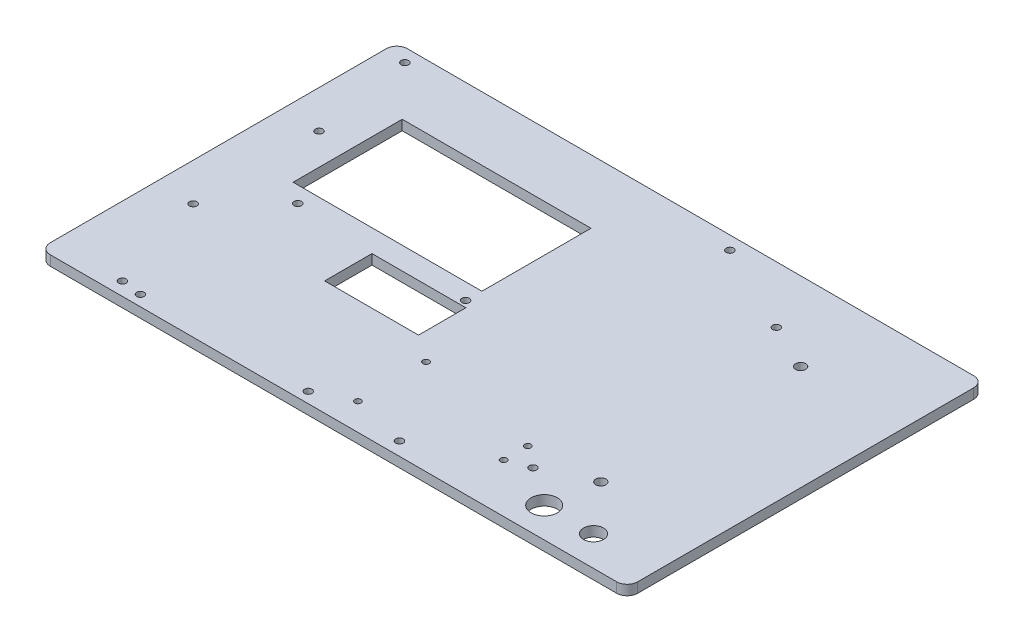
SolidWorks part; units mm, degrees
material "Acrylic (Medium-high impact)"
ref_plane "Front Plane" through (0, 0, 0) normal (0, 0, 1) x (1, 0, 0)
ref_plane "Top Plane" through (0, 0, 0) normal (0, 1, 0) x (1, 0, 0)
ref_plane "Right Plane" through (0, 0, 0) normal (1, 0, 0) x (0, 0, -1)
sketch "Sketch1" plane through (0, 0, 0) normal (0, 1, 0) x (1, 0, 0)
  line L1 (-135, 85.09) -> (135, 85.09)
  line L2 (-140, 80.09) -> (-140, -80.09)
  line L3 (-135, -85.09) -> (135, -85.09)
  line L4 (140, 80.09) -> (140, -80.09)
  line L5 (-140, 85.09) -> (140, -85.09) construction
  line L6 (-140, -85.09) -> (140, 85.09) construction
  arc A0 (-135, 85.09) -> (-140, 80.09) centre (-135, 80.09) ccw
  arc A1 (-140, -80.09) -> (-135, -85.09) centre (-135, -80.09) ccw
  arc A2 (135, -85.09) -> (140, -80.09) centre (135, -80.09) ccw
  arc A3 (135, 85.09) -> (140, 80.09) centre (135, 80.09) cw
  point P0 (0, 0)
  dimension "D3" = 5
  dimension "D1" = 170.18
  dimension "D2" = 280
extrude "Boss-Extrude1" add sketch "Sketch1" along normal blind 4.7625
sketch "Sketch2" plane through (0, 0, 0) normal (0, 1, 0) x (1, 0, 0)
  line L0 (-122, 30) -> (-122, -30) construction
  line L1 (68, 58) -> (68, -58) construction
  line L2 (-140, 80.09) -> (-140, -80.09) construction
  line L3 (140, -80.09) -> (140, 80.09) construction
  circle A0 centre (68, 58) radius 1.778
  circle A1 centre (68, -58) radius 1.778
  circle A2 centre (-122, 30) radius 1.778
  circle A3 centre (-122, -30) radius 1.778
  point P10 (-140, 0)
  point P11 (-122, 0)
  point P12 (68, 0)
  point P15 (140, 0)
  dimension "D3" = 3.556
  dimension "D1" = 116
  dimension "D2" = 60
  dimension "D4" = 190
  dimension "D5" = 18
extrude "chassis standoff" cut sketch "Sketch2" along normal through all
sketch "Sketch3" plane through (0, 0, 0) normal (0, 1, 0) x (1, 0, 0)
  line L0 (-1.2288, -39.7403) -> (-1.2288, -72.2403) construction
  line L1 (57.7712, -50.2403) -> (57.7712, -61.7403) construction
  line L2 (-4.2288, -36.7403) -> (60.7712, -36.7403) construction
  line L3 (60.7712, -36.7403) -> (60.7712, -75.2403) construction
  line L4 (60.7712, -75.2403) -> (-4.2288, -75.2403) construction
  line L5 (-4.2288, -75.2403) -> (-4.2288, -69.2403) construction
  line L6 (-4.2288, -69.2403) -> (1.7712, -69.2403) construction
  line L7 (1.7712, -69.2403) -> (1.7712, -42.7403) construction
  line L8 (1.7712, -42.7403) -> (-4.2288, -42.7403) construction
  line L9 (-4.2288, -42.7403) -> (-4.2288, -36.7403) construction
  circle A0 centre (57.7712, -50.2403) radius 1.5
  circle A1 centre (57.7712, -61.7403) radius 1.5
  circle A2 centre (-1.2288, -39.7403) radius 1.5
  circle A3 centre (-1.2288, -72.2403) radius 1.5
  point P8 (-1.2288, -55.9903)
  point P9 (57.7712, -55.9903)
  dimension "D1" = 3
  dimension "D2" = 11.5
  dimension "D3" = 32.5
  dimension "D4" = 59
  dimension "D5" = 3
  dimension "D6" = 3
  dimension "D7" = 3
  dimension "D8" = 3
  dimension "D9" = 3
  dimension "D10" = 3
  dimension "D11" = 3
  dimension "D12" = 3
extrude "vesc" cut sketch "Sketch3" along normal through all
sketch "Sketch13" plane through (0, 0, 0) normal (0, 1, 0) x (1, 0, 0)
  line L1 (-102.17, 0.053) -> (-12.17, 0.053) construction
  line L2 (-102.17, 0.053) -> (-102.17, -84.947) construction
  line L3 (-102.17, -84.947) -> (-12.17, -84.947) construction
  line L4 (-12.17, 0.053) -> (-12.17, -84.947) construction
  line L5 (-102.17, 0.053) -> (-12.17, -84.947) construction
  line L6 (-102.17, -84.947) -> (-12.17, 0.053) construction
  line L8 (-58.8343, -7.9166) -> (-58.8343, -30.4863)
  line L9 (-58.8343, -30.4863) -> (-14.0785, -30.4863)
  line L10 (-14.0785, -7.9166) -> (-14.0785, -30.4863)
  line L15 (-14.0785, -7.9166) -> (-58.8343, -7.9166)
  circle A0 centre (-97.17, -4.947) radius 1.778
  circle A1 centre (-17.17, -4.947) radius 1.778
  circle A2 centre (-17.17, -79.947) radius 1.778
  circle A3 centre (-97.17, -79.947) radius 1.778
  point P15 (-57.17, -42.447)
  point P20 (-92.17, -10.0483)
  point P26 (-22.17, -10.0483)
  dimension "D1" = 3.556
  dimension "D2" = 85
  dimension "D3" = 90
  dimension "D4" = 5
  dimension "D5" = 5
  dimension "D6" = 5
  dimension "D7" = 5
extrude "pcb" cut sketch "Sketch13" along normal through all
sketch "Sketch6" plane through (0, 0, 0) normal (0, 1, 0) x (1, 0, 0)
  line L0 (-140, 80.09) -> (-140, -80.09) construction
  line L1 (-140, 85.09) -> (30.18, 85.09) construction
  line L2 (-140, 85.09) -> (-140, -85.09) construction
  line L3 (-140, -85.09) -> (30.18, -85.09) construction
  line L4 (30.18, 85.09) -> (30.18, -85.09) construction
  line L6 (-107.08, 2.74) -> (-17.08, 2.74)
  line L7 (-107.08, 2.74) -> (-107.08, 54.74)
  line L8 (-107.08, 54.74) -> (-17.08, 54.74)
  line L9 (-17.08, 2.74) -> (-17.08, 54.74)
  line L10 (-101.58, 49.74) -> (-22.58, 49.74) construction
  line L11 (-101.58, 49.74) -> (-101.58, 7.74) construction
  line L12 (-101.58, 7.74) -> (-22.58, 7.74) construction
  line L13 (-22.58, 49.74) -> (-22.58, 7.74) construction
  point P14 (-140, 0)
  point P15 (-140, 0)
  point P16 (-62.08, 54.74)
  point P17 (-62.08, 49.74)
  point P18 (-101.58, 28.74)
  point P19 (-107.08, 28.74)
  dimension "D1" = 52
  dimension "D2" = 90
  dimension "D3" = 42
  dimension "D4" = 170.18
  dimension "D5" = 79
  dimension "D6" = 52.76
  dimension "D8" = 35.35
extrude "jetson" cut sketch "Sketch6" along normal through all
sketch "Sketch12" plane through (0, 0, 0) normal (0, 1, 0) x (1, 0, 0)
  line L0 (-140, 85.09) -> (30.18, 85.09) construction
  line L3 (-140, -85.09) -> (30.18, -85.09) construction
  line L5 (30.18, 85.09) -> (30.18, -85.09) construction
  line L6 (-140, 85.09) -> (-140, -85.09) construction
  circle A0 centre (-129.82, 78.74) radius 1.778
  circle A1 centre (-106.98, -78.74) radius 1.778
  circle A2 centre (25.1, 78.74) radius 1.778
  circle A3 centre (25.1, -78.74) radius 1.778
  dimension "D1" = 3.556
  dimension "D2" = 6.35
  dimension "D3" = 6.35
  dimension "D4" = 5.08
  dimension "D5" = 10.18
  dimension "D6" = 33.02
extrude "top plate standoff" cut sketch "Sketch12" along normal through all
sketch "Sketch14" plane through (0, 0, 0) normal (0, 1, 0) x (1, 0, 0)
  line L0 (140, -80.09) -> (140, 80.09) construction
  line L1 (48.1346, 41.8465) -> (131.8276, 41.8465) construction
  line L2 (48.1346, 41.8465) -> (48.1346, -41.8465) construction
  line L3 (48.1346, -41.8465) -> (131.8276, -41.8465) construction
  line L4 (131.8276, 41.8465) -> (131.8276, -41.8465) construction
  line L5 (48.1346, 41.8465) -> (131.8276, -41.8465) construction
  line L6 (48.1346, -41.8465) -> (131.8276, 41.8465) construction
  line L7 (89.9811, 47.625) -> (89.9811, -47.625) construction
  circle A0 centre (89.9811, 47.625) radius 2.413
  circle A1 centre (89.9811, -47.625) radius 2.413
  point P0 (89.9811, 0)
  point P8 (140, 0)
  dimension "D2" = 4.826
  dimension "D1" = 83.693
  dimension "D3" = 95.25
extrude "velodyne interface box" cut sketch "Sketch14" along normal through all
sketch "Sketch16" plane through (0, 0, 0) normal (0, 1, 0) x (1, 0, 0)
  circle A0 centre (86.1411, -70.7825) radius 6.25
  circle A1 centre (109.6444, -70.7825) radius 4.7625
  dimension "D1" = 9.525
  dimension "D2" = 12.5
extrude "switch" cut sketch "Sketch16" along normal through all
sketch "Sketch4" plane through (0, 0, 0) normal (0, 1, 0) x (1, 0, 0)
  line L0 (140, -80.09) -> (140, 80.09) construction
  line L1 (97.7048, 20) -> (137.7048, 20) construction
  line L2 (97.7048, 20) -> (97.7048, -20) construction
  line L3 (97.7048, -20) -> (137.7048, -20) construction
  line L4 (137.7048, 20) -> (137.7048, -20) construction
  line L5 (97.7048, 20) -> (137.7048, -20) construction
  line L6 (97.7048, -20) -> (137.7048, 20) construction
  line L8 (92.7048, 25) -> (142.7048, 25) construction
  line L9 (92.7048, 25) -> (92.7048, -25) construction
  line L10 (92.7048, -25) -> (142.7048, -25) construction
  line L11 (142.7048, 25) -> (142.7048, -25) construction
  line L12 (92.7048, 25) -> (142.7048, -25) construction
  line L13 (92.7048, -25) -> (142.7048, 25) construction
  circle A0 centre (97.7048, 20) radius 1.59
  circle A1 centre (97.7048, -20) radius 1.59
  circle A2 centre (137.7048, -20) radius 1.59
  circle A3 centre (137.7048, 20) radius 1.59
  point P0 (117.7048, 0)
  point P22 (140, 0)
  point P23 (137.7048, 0)
  point P25 (117.7048, 0)
  dimension "D1" = 3.18
  dimension "D2" = 40
  dimension "D3" = 50
extrude "lidar urg/ust" [suppressed] cut sketch "Sketch4" along normal through all
sketch "Sketch9" plane through (0, 0, 0) normal (0, 1, 0) x (1, 0, 0)
  line L0 (140, -80.09) -> (140, 80.09) construction
  line L1 (85.1536, 26.5) -> (138.1536, 26.5) construction
  line L2 (85.1536, 26.5) -> (85.1536, -26.5) construction
  line L3 (85.1536, -26.5) -> (138.1536, -26.5) construction
  line L4 (138.1536, 26.5) -> (138.1536, -26.5) construction
  line L5 (85.1536, 26.5) -> (138.1536, -26.5) construction
  line L6 (85.1536, -26.5) -> (138.1536, 26.5) construction
  line L7 (80.6536, 31) -> (142.6536, 31) construction
  line L8 (80.6536, 31) -> (80.6536, -31) construction
  line L9 (80.6536, -31) -> (142.6536, -31) construction
  line L10 (142.6536, 31) -> (142.6536, -31) construction
  line L11 (80.6536, 31) -> (142.6536, -31) construction
  line L12 (80.6536, -31) -> (142.6536, 31) construction
  circle A0 centre (138.1536, 26.5) radius 1.59
  circle A1 centre (138.1536, -26.5) radius 1.59
  circle A2 centre (85.1536, -26.5) radius 1.59
  circle A3 centre (85.1536, 26.5) radius 1.59
  point P0 (111.6536, 0)
  point P9 (111.6536, 0)
  point P19 (140, 0)
  dimension "D1" = 3.18
  dimension "D2" = 53
  dimension "D3" = 62
extrude "lidar utm" [suppressed] cut sketch "Sketch9" along normal through all
sketch "Sketch5" [suppressed] plane through (0, 0, 0) normal (0, 1, 0) x (1, 0, 0)
  line L0 (143, -60) -> (143, 60) construction
  circle A0 centre (89.529, 0) radius 3.3
  circle A1 centre (89.529, 0) radius 51.65 construction
  point P6 (143, 0)
  dimension "D1" = 6.6
  dimension "D2" = 103.3
extrude "lidar velodyne" [suppressed] cut sketch "Sketch5" along normal through all
sketch "Sketch10" plane through (0, 0, 0) normal (0, 1, 0) x (1, 0, 0)
  line L0 (135, 85.09) -> (-135, 85.09) construction
  line L1 (-135, -85.09) -> (135, -85.09) construction
  line L2 (-140, 80.09) -> (-140, -80.09) construction
  line L3 (140, -80.09) -> (140, 80.09) construction
  line L4 (140, -80.09) -> (140, 80.09)
  line L5 (-140, 0) -> (-140, -80.09)
  line L6 (24.4467, -85.09) -> (135, -85.09)
  line L7 (135, 85.09) -> (24.4467, 85.09)
  line L8 (-140, 0) -> (140, 0) construction
  arc A0 (140, 80.09) -> (135, 85.09) centre (135, 80.09) ccw construction
  arc A1 (135, -85.09) -> (140, -80.09) centre (135, -80.09) ccw construction
  arc A6 (140, 80.09) -> (135, 85.09) centre (135, 80.09) ccw
  arc A7 (135, -85.09) -> (140, -80.09) centre (135, -80.09) ccw
  spline S0 degree 3 poles (24.4467, 85.09) (70.9272, 85.09) (110.0921, 59.3739) (140, 27.2863) knots 0 0 0 0 1 1 1 1
  spline S1 degree 3 poles (24.4467, -85.09) (70.9272, -85.09) (110.0921, -59.3739) (140, -27.2863) knots 0 0 0 0 1 1 1 1
extrude "Cut-Extrude9" [suppressed] cut sketch "Sketch10" along normal through all contours L7 S0 L4 A6 | S1 L6 A7 L4
sketch "Sketch11" plane through (0, 0, 0) normal (0, 1, 0) x (1, 0, 0)
  line L2 (135, 85.09) -> (-135, 85.09) construction
  line L3 (140, 80.09) -> (140, 30.4727)
  line L4 (-140, 0) -> (142.7048, 0) construction
  line L5 (135, 85.09) -> (79.4863, 85.09)
  line L6 (81.6386, 83.9588) -> (142.301, 29.7244)
  line L7 (-140, 80.09) -> (-140, -80.09) construction
  line L8 (142.7048, 25) -> (142.7048, -25) construction
  line L9 (135, -85.09) -> (79.4863, -85.09)
  line L10 (140, -80.09) -> (140, -30.4727)
  line L11 (81.6386, -83.9588) -> (142.301, -29.7244)
  arc A1 (140, 80.09) -> (135, 85.09) centre (135, 80.09) ccw construction
  arc A2 (140, -30.4727) -> (142.301, -29.7244) centre (140.3014, -27.4879) cw
  arc A3 (140, 80.09) -> (135, 85.09) centre (135, 80.09) ccw
  arc A4 (81.6386, 83.9588) -> (79.4863, 85.09) centre (78.3061, 80.2313) ccw
  arc A5 (140, 30.4727) -> (142.301, 29.7244) centre (140.3014, 27.4879) ccw
  arc A6 (81.6386, -83.9588) -> (79.4863, -85.09) centre (78.3061, -80.2313) cw
  arc A7 (140, -80.09) -> (135, -85.09) centre (135, -80.09) cw
  dimension "D1" = 5
  dimension "D2" = 3
extrude "Cut-Extrude10" [suppressed] cut sketch "Sketch11" along normal through all
